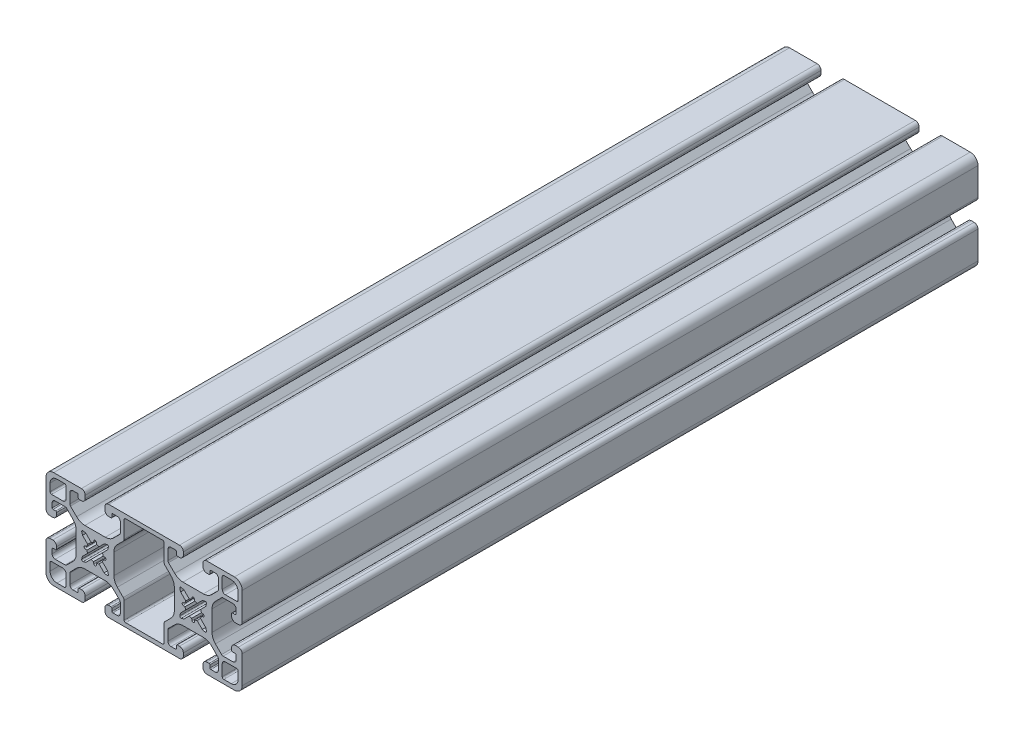
SolidWorks part; units mm, degrees
material "6105-T5 Aluminum"
ref_plane "Front Plane" through (0, 0, 0) normal (0, 0, 1) x (1, 0, 0)
ref_plane "Top Plane" through (0, 0, 0) normal (0, 1, 0) x (1, 0, 0)
ref_plane "Right Plane" through (0, 0, 0) normal (1, 0, 0) x (0, 0, -1)
sketch "Sketch1" plane through (0, 0, 0) normal (0, 0, 1) x (1, 0, 0)
  line L0 (-24, -18.4848) -> (-24, -17.255)
  line L1 (-26.474, -15.685) -> (-25.57, -15.685)
  line L2 (-36.83, -20) -> (-25.569, -20)
  line L3 (-26.855, -17.119) -> (-26.855, -16.066)
  line L4 (-40, -16.83) -> (-40, -5.57)
  line L5 (-29.015, -17.5) -> (-27.236, -17.5)
  line L6 (-38.43, -4) -> (-37.255, -4)
  line L7 (-30.285, -16.23) -> (-30.285, -12.2162)
  line L8 (-35.685, -5.57) -> (-35.685, -6.474)
  line L9 (-27.5137, -9.0762) -> (-30.0243, -11.5869)
  line L10 (-37.119, -6.855) -> (-36.066, -6.855)
  line L11 (-24.1549, -7.685) -> (-15.8451, -7.685)
  line L12 (-37.5, -9.015) -> (-37.5, -7.236)
  line L13 (-12.4863, -9.0762) -> (-9.9757, -11.5869)
  line L14 (-36.23, -10.285) -> (-32.2162, -10.285)
  line L15 (-9.715, -16.23) -> (-9.715, -12.2162)
  line L16 (-29.0762, -7.5137) -> (-31.5869, -10.0243)
  line L17 (-10.985, -17.5) -> (-12.764, -17.5)
  line L18 (-27.685, 4.1549) -> (-27.685, -4.1549)
  line L19 (-13.145, -17.119) -> (-13.145, -16.066)
  line L20 (-29.0762, 7.5137) -> (-31.5869, 10.0243)
  line L21 (-14.43, -15.685) -> (-13.526, -15.685)
  line L22 (-36.23, 10.285) -> (-32.2162, 10.285)
  line L23 (-16, -18.4848) -> (-16, -17.255)
  line L24 (-37.5, 9.015) -> (-37.5, 7.236)
  line L25 (14.43, -20) -> (-14.431, -20)
  line L26 (-37.119, 6.855) -> (-36.066, 6.855)
  line L27 (16, -17.255) -> (16, -18.43)
  line L28 (-35.685, 6.474) -> (-35.685, 5.57)
  line L29 (14.43, -15.685) -> (13.526, -15.685)
  line L30 (-38.43, 4) -> (-37.255, 4)
  line L31 (13.145, -17.119) -> (13.145, -16.066)
  line L32 (-40, 16.83) -> (-40, 5.57)
  line L33 (10.985, -17.5) -> (12.764, -17.5)
  line L34 (-36.83, 20) -> (-25.57, 20)
  line L35 (9.715, -16.23) -> (9.715, -12.2162)
  line L36 (-24, 18.43) -> (-24, 17.255)
  line L37 (12.4863, -9.0762) -> (9.9757, -11.5869)
  line L38 (-25.57, 15.685) -> (-26.474, 15.685)
  line L39 (24.1549, -7.685) -> (15.8451, -7.685)
  line L40 (-26.855, 17.119) -> (-26.855, 16.066)
  line L41 (27.5137, -9.0762) -> (30.0243, -11.5869)
  line L42 (-29.015, 17.5) -> (-27.236, 17.5)
  line L43 (30.285, -16.23) -> (30.285, -12.2162)
  line L44 (-30.285, 16.23) -> (-30.285, 12.2162)
  line L45 (29.015, -17.5) -> (27.236, -17.5)
  line L46 (-27.5137, 9.0762) -> (-30.0243, 11.5869)
  line L47 (26.855, -17.119) -> (26.855, -16.066)
  line L48 (-15.8451, 7.685) -> (-24.1549, 7.685)
  line L49 (26.474, -15.685) -> (25.57, -15.685)
  line L50 (-12.4863, 9.0762) -> (-9.9757, 11.5869)
  line L51 (24, -17.255) -> (24, -18.43)
  line L52 (-9.715, 16.23) -> (-9.715, 12.2162)
  line L53 (36.83, -20) -> (25.57, -20)
  line L54 (-10.985, 17.5) -> (-12.764, 17.5)
  line L55 (40, -16.83) -> (40, -5.57)
  line L56 (-13.145, 17.119) -> (-13.145, 16.066)
  line L57 (37.255, -4) -> (38.43, -4)
  line L58 (-13.526, 15.685) -> (-14.43, 15.685)
  line L59 (35.685, -5.57) -> (35.685, -6.474)
  line L60 (-16, 18.43) -> (-16, 17.255)
  line L61 (37.119, -6.855) -> (36.066, -6.855)
  line L62 (-14.43, 20) -> (14.43, 20)
  line L63 (37.5, -9.015) -> (37.5, -7.236)
  line L64 (16, 18.43) -> (16, 17.255)
  line L65 (36.23, -10.285) -> (32.2162, -10.285)
  line L66 (13.526, 15.685) -> (14.43, 15.685)
  line L67 (29.0762, -7.5137) -> (31.5869, -10.0243)
  line L68 (13.145, 17.119) -> (13.145, 16.066)
  line L69 (27.685, 4.1549) -> (27.685, -4.1549)
  line L70 (10.985, 17.5) -> (12.764, 17.5)
  line L71 (29.0762, 7.5137) -> (31.5869, 10.0243)
  line L72 (9.715, 16.23) -> (9.715, 12.2162)
  line L73 (36.23, 10.285) -> (32.2162, 10.285)
  line L74 (12.4863, 9.0762) -> (9.9757, 11.5869)
  line L75 (37.5, 9.015) -> (37.5, 7.236)
  line L76 (15.8451, 7.685) -> (24.1549, 7.685)
  line L77 (37.119, 6.855) -> (36.066, 6.855)
  line L78 (27.5137, 9.0762) -> (30.0243, 11.5869)
  line L79 (35.685, 6.474) -> (35.685, 5.57)
  line L80 (30.285, 16.23) -> (30.285, 12.2162)
  line L81 (37.255, 4) -> (38.43, 4)
  line L82 (29.015, 17.5) -> (27.236, 17.5)
  line L83 (40, 16.83) -> (40, 5.57)
  line L84 (26.855, 17.119) -> (26.855, 16.066)
  line L85 (36.83, 20) -> (25.57, 20)
  line L86 (25.57, 15.685) -> (26.474, 15.685)
  line L87 (24, 18.43) -> (24, 17.255)
  line L88 (35.545, -18.345) -> (32.4898, -18.345)
  line L89 (38.345, -12.4898) -> (38.345, -15.545)
  line L90 (31.8598, -17.715) -> (31.8598, -13.1298)
  line L91 (33.1298, -11.8598) -> (37.715, -11.8598)
  line L92 (8.1402, 17.715) -> (8.1402, 10.8233)
  line L93 (8.5122, 9.9253) -> (10.9238, 7.5137)
  line L94 (-7.5102, 18.345) -> (7.5102, 18.345)
  line L95 (12.315, 4.1549) -> (12.315, -4.1549)
  line L96 (-8.1402, 10.8233) -> (-8.1402, 17.715)
  line L97 (10.9238, -7.5137) -> (8.5122, -9.9253)
  line L98 (-10.9238, 7.5137) -> (-8.5122, 9.9253)
  line L99 (8.1402, -10.8233) -> (8.1402, -17.715)
  line L100 (-12.315, -4.1549) -> (-12.315, 4.1549)
  line L101 (7.5102, -18.345) -> (-7.5102, -18.345)
  line L102 (-8.5122, -9.9253) -> (-10.9238, -7.5137)
  line L103 (-8.1402, -17.715) -> (-8.1402, -10.8233)
  line L104 (-38.345, -15.545) -> (-38.345, -12.4898)
  line L105 (-32.4898, -18.345) -> (-35.545, -18.345)
  line L106 (-37.715, -11.8598) -> (-33.1298, -11.8598)
  line L107 (-31.8598, -13.1298) -> (-31.8598, -17.715)
  line L108 (-35.545, 18.345) -> (-32.4898, 18.345)
  line L109 (-38.345, 12.4898) -> (-38.345, 15.545)
  line L110 (-31.8598, 17.715) -> (-31.8598, 13.1298)
  line L111 (-33.1298, 11.8598) -> (-37.715, 11.8598)
  line L112 (38.345, 15.545) -> (38.345, 12.4898)
  line L113 (32.4898, 18.345) -> (35.545, 18.345)
  line L114 (37.715, 11.8598) -> (33.1298, 11.8598)
  line L115 (31.8598, 13.1298) -> (31.8598, 17.715)
  line L116 (-14.8737, -3.712) -> (-14.5607, -4.8481)
  line L117 (-16.9951, -1.5907) -> (-14.8737, -3.712)
  line L118 (-15.1519, -5.4393) -> (-16.288, -5.1263)
  line L119 (-16.288, -5.1263) -> (-18.4093, -3.0049)
  line L120 (-15.9124, -0.4923) -> (-16.6579, -0.625)
  line L121 (-19.375, -3.3421) -> (-19.5077, -4.0876)
  line L122 (-16.6579, 0.625) -> (-15.9124, 0.4923)
  line L123 (-20.4923, -4.0876) -> (-20.625, -3.3421)
  line L124 (-14.8737, 3.712) -> (-16.9951, 1.5907)
  line L125 (-14.5607, 4.8481) -> (-14.8737, 3.712)
  line L126 (-21.5907, -3.0049) -> (-23.712, -5.1263)
  line L127 (-23.712, -5.1263) -> (-24.8481, -5.4393)
  line L128 (-16.288, 5.1263) -> (-15.1519, 5.4393)
  line L129 (-18.4093, 3.0049) -> (-16.288, 5.1263)
  line L130 (-25.4393, -4.8481) -> (-25.1263, -3.712)
  line L131 (-25.1263, -3.712) -> (-23.0049, -1.5907)
  line L132 (-19.5077, 4.0876) -> (-19.375, 3.3421)
  line L133 (-23.3421, -0.625) -> (-24.0876, -0.4923)
  line L134 (-20.625, 3.3421) -> (-20.4923, 4.0876)
  line L135 (-24.0876, 0.4923) -> (-23.3421, 0.625)
  line L136 (-23.712, 5.1263) -> (-21.5907, 3.0049)
  line L137 (-24.8481, 5.4393) -> (-23.712, 5.1263)
  line L138 (-23.0049, 1.5907) -> (-25.1263, 3.712)
  line L139 (-25.1263, 3.712) -> (-25.4393, 4.8481)
  line L140 (25.1263, -3.712) -> (25.4393, -4.8481)
  line L141 (23.0049, -1.5907) -> (25.1263, -3.712)
  line L142 (24.8481, -5.4393) -> (23.712, -5.1263)
  line L143 (23.712, -5.1263) -> (21.5907, -3.0049)
  line L144 (24.0876, -0.4923) -> (23.3421, -0.625)
  line L145 (20.625, -3.3421) -> (20.4923, -4.0876)
  line L146 (23.3421, 0.625) -> (24.0876, 0.4923)
  line L147 (19.5077, -4.0876) -> (19.375, -3.3421)
  line L148 (25.1263, 3.712) -> (23.0049, 1.5907)
  line L149 (25.4393, 4.8481) -> (25.1263, 3.712)
  line L150 (18.4093, -3.0049) -> (16.288, -5.1263)
  line L151 (16.288, -5.1263) -> (15.1519, -5.4393)
  line L152 (23.712, 5.1263) -> (24.8481, 5.4393)
  line L153 (21.5907, 3.0049) -> (23.712, 5.1263)
  line L154 (14.5607, -4.8481) -> (14.8737, -3.712)
  line L155 (14.8737, -3.712) -> (16.9951, -1.5907)
  line L156 (20.4923, 4.0876) -> (20.625, 3.3421)
  line L157 (16.6579, -0.625) -> (15.9124, -0.4923)
  line L158 (19.375, 3.3421) -> (19.5077, 4.0876)
  line L159 (15.9124, 0.4923) -> (16.6579, 0.625)
  line L160 (16.288, 5.1263) -> (18.4093, 3.0049)
  line L161 (15.1519, 5.4393) -> (16.288, 5.1263)
  line L162 (16.9951, 1.5907) -> (14.8737, 3.712)
  line L163 (14.8737, 3.712) -> (14.5607, 4.8481)
  arc A0 (-24, -17.255) -> (-25.57, -15.685) centre (-25.57, -17.255) ccw
  arc A1 (-25.569, -20) -> (-24, -18.4848) centre (-25.569, -18.43) ccw
  arc A2 (-26.474, -15.685) -> (-26.855, -16.066) centre (-26.474, -16.066) ccw
  arc A3 (-40, -16.83) -> (-36.83, -20) centre (-36.83, -16.83) ccw
  arc A4 (-27.236, -17.5) -> (-26.855, -17.119) centre (-27.236, -17.119) ccw
  arc A5 (-38.43, -4) -> (-40, -5.57) centre (-38.43, -5.57) ccw
  arc A6 (-30.285, -16.23) -> (-29.015, -17.5) centre (-29.015, -16.23) ccw
  arc A7 (-35.685, -5.57) -> (-37.255, -4) centre (-37.255, -5.57) ccw
  arc A8 (-30.0243, -11.5869) -> (-30.285, -12.2162) centre (-29.395, -12.2162) ccw
  arc A9 (-36.066, -6.855) -> (-35.685, -6.474) centre (-36.066, -6.474) ccw
  arc A10 (-24.1549, -7.685) -> (-27.5137, -9.0762) centre (-24.1549, -12.435) ccw
  arc A11 (-37.119, -6.855) -> (-37.5, -7.236) centre (-37.119, -7.236) ccw
  arc A12 (-12.4863, -9.0762) -> (-15.8451, -7.685) centre (-15.8451, -12.435) ccw
  arc A13 (-37.5, -9.015) -> (-36.23, -10.285) centre (-36.23, -9.015) ccw
  arc A14 (-9.715, -12.2162) -> (-9.9757, -11.5869) centre (-10.605, -12.2162) ccw
  arc A15 (-32.2162, -10.285) -> (-31.5869, -10.0243) centre (-32.2162, -9.395) ccw
  arc A16 (-10.985, -17.5) -> (-9.715, -16.23) centre (-10.985, -16.23) ccw
  arc A17 (-29.0762, -7.5137) -> (-27.685, -4.1549) centre (-32.435, -4.1549) ccw
  arc A18 (-13.145, -17.119) -> (-12.764, -17.5) centre (-12.764, -17.119) ccw
  arc A19 (-27.685, 4.1549) -> (-29.0762, 7.5137) centre (-32.435, 4.1549) ccw
  arc A20 (-13.145, -16.066) -> (-13.526, -15.685) centre (-13.526, -16.066) ccw
  arc A21 (-31.5869, 10.0243) -> (-32.2162, 10.285) centre (-32.2162, 9.395) ccw
  arc A22 (-14.43, -15.685) -> (-16, -17.255) centre (-14.43, -17.255) ccw
  arc A23 (-36.23, 10.285) -> (-37.5, 9.015) centre (-36.23, 9.015) ccw
  arc A24 (-16, -18.4848) -> (-14.431, -20) centre (-14.431, -18.43) ccw
  arc A25 (-37.5, 7.236) -> (-37.119, 6.855) centre (-37.119, 7.236) ccw
  arc A26 (14.43, -20) -> (16, -18.43) centre (14.43, -18.43) ccw
  arc A27 (-35.685, 6.474) -> (-36.066, 6.855) centre (-36.066, 6.474) ccw
  arc A28 (16, -17.255) -> (14.43, -15.685) centre (14.43, -17.255) ccw
  arc A29 (-37.255, 4) -> (-35.685, 5.57) centre (-37.255, 5.57) ccw
  arc A30 (13.526, -15.685) -> (13.145, -16.066) centre (13.526, -16.066) ccw
  arc A31 (-40, 5.57) -> (-38.43, 4) centre (-38.43, 5.57) ccw
  arc A32 (12.764, -17.5) -> (13.145, -17.119) centre (12.764, -17.119) ccw
  arc A33 (-36.83, 20) -> (-40, 16.83) centre (-36.83, 16.83) ccw
  arc A34 (9.715, -16.23) -> (10.985, -17.5) centre (10.985, -16.23) ccw
  arc A35 (-24, 18.43) -> (-25.57, 20) centre (-25.57, 18.43) ccw
  arc A36 (9.9757, -11.5869) -> (9.715, -12.2162) centre (10.605, -12.2162) ccw
  arc A37 (-25.57, 15.685) -> (-24, 17.255) centre (-25.57, 17.255) ccw
  arc A38 (15.8451, -7.685) -> (12.4863, -9.0762) centre (15.8451, -12.435) ccw
  arc A39 (-26.855, 16.066) -> (-26.474, 15.685) centre (-26.474, 16.066) ccw
  arc A40 (27.5137, -9.0762) -> (24.1549, -7.685) centre (24.1549, -12.435) ccw
  arc A41 (-26.855, 17.119) -> (-27.236, 17.5) centre (-27.236, 17.119) ccw
  arc A42 (30.285, -12.2162) -> (30.0243, -11.5869) centre (29.395, -12.2162) ccw
  arc A43 (-29.015, 17.5) -> (-30.285, 16.23) centre (-29.015, 16.23) ccw
  arc A44 (29.015, -17.5) -> (30.285, -16.23) centre (29.015, -16.23) ccw
  arc A45 (-30.285, 12.2162) -> (-30.0243, 11.5869) centre (-29.395, 12.2162) ccw
  arc A46 (26.855, -17.119) -> (27.236, -17.5) centre (27.236, -17.119) ccw
  arc A47 (-27.5137, 9.0762) -> (-24.1549, 7.685) centre (-24.1549, 12.435) ccw
  arc A48 (26.855, -16.066) -> (26.474, -15.685) centre (26.474, -16.066) ccw
  arc A49 (-15.8451, 7.685) -> (-12.4863, 9.0762) centre (-15.8451, 12.435) ccw
  arc A50 (25.57, -15.685) -> (24, -17.255) centre (25.57, -17.255) ccw
  arc A51 (-9.9757, 11.5869) -> (-9.715, 12.2162) centre (-10.605, 12.2162) ccw
  arc A52 (24, -18.43) -> (25.57, -20) centre (25.57, -18.43) ccw
  arc A53 (-9.715, 16.23) -> (-10.985, 17.5) centre (-10.985, 16.23) ccw
  arc A54 (36.83, -20) -> (40, -16.83) centre (36.83, -16.83) ccw
  arc A55 (-12.764, 17.5) -> (-13.145, 17.119) centre (-12.764, 17.119) ccw
  arc A56 (40, -5.57) -> (38.43, -4) centre (38.43, -5.57) ccw
  arc A57 (-13.526, 15.685) -> (-13.145, 16.066) centre (-13.526, 16.066) ccw
  arc A58 (37.255, -4) -> (35.685, -5.57) centre (37.255, -5.57) ccw
  arc A59 (-16, 17.255) -> (-14.43, 15.685) centre (-14.43, 17.255) ccw
  arc A60 (35.685, -6.474) -> (36.066, -6.855) centre (36.066, -6.474) ccw
  arc A61 (-14.43, 20) -> (-16, 18.43) centre (-14.43, 18.43) ccw
  arc A62 (37.5, -7.236) -> (37.119, -6.855) centre (37.119, -7.236) ccw
  arc A63 (16, 18.43) -> (14.43, 20) centre (14.43, 18.43) ccw
  arc A64 (36.23, -10.285) -> (37.5, -9.015) centre (36.23, -9.015) ccw
  arc A65 (14.43, 15.685) -> (16, 17.255) centre (14.43, 17.255) ccw
  arc A66 (31.5869, -10.0243) -> (32.2162, -10.285) centre (32.2162, -9.395) ccw
  arc A67 (13.145, 16.066) -> (13.526, 15.685) centre (13.526, 16.066) ccw
  arc A68 (27.685, -4.1549) -> (29.0762, -7.5137) centre (32.435, -4.1549) ccw
  arc A69 (13.145, 17.119) -> (12.764, 17.5) centre (12.764, 17.119) ccw
  arc A70 (29.0762, 7.5137) -> (27.685, 4.1549) centre (32.435, 4.1549) ccw
  arc A71 (10.985, 17.5) -> (9.715, 16.23) centre (10.985, 16.23) ccw
  arc A72 (32.2162, 10.285) -> (31.5869, 10.0243) centre (32.2162, 9.395) ccw
  arc A73 (9.715, 12.2162) -> (9.9757, 11.5869) centre (10.605, 12.2162) ccw
  arc A74 (37.5, 9.015) -> (36.23, 10.285) centre (36.23, 9.015) ccw
  arc A75 (12.4863, 9.0762) -> (15.8451, 7.685) centre (15.8451, 12.435) ccw
  arc A76 (37.119, 6.855) -> (37.5, 7.236) centre (37.119, 7.236) ccw
  arc A77 (24.1549, 7.685) -> (27.5137, 9.0762) centre (24.1549, 12.435) ccw
  arc A78 (36.066, 6.855) -> (35.685, 6.474) centre (36.066, 6.474) ccw
  arc A79 (30.0243, 11.5869) -> (30.285, 12.2162) centre (29.395, 12.2162) ccw
  arc A80 (35.685, 5.57) -> (37.255, 4) centre (37.255, 5.57) ccw
  arc A81 (30.285, 16.23) -> (29.015, 17.5) centre (29.015, 16.23) ccw
  arc A82 (38.43, 4) -> (40, 5.57) centre (38.43, 5.57) ccw
  arc A83 (27.236, 17.5) -> (26.855, 17.119) centre (27.236, 17.119) ccw
  arc A84 (40, 16.83) -> (36.83, 20) centre (36.83, 16.83) ccw
  arc A85 (26.474, 15.685) -> (26.855, 16.066) centre (26.474, 16.066) ccw
  arc A86 (25.57, 20) -> (24, 18.43) centre (25.57, 18.43) ccw
  arc A87 (24, 17.255) -> (25.57, 15.685) centre (25.57, 17.255) ccw
  arc A88 (35.545, -18.345) -> (38.345, -15.545) centre (35.545, -15.545) ccw
  arc A89 (31.8598, -17.715) -> (32.4898, -18.345) centre (32.4898, -17.715) ccw
  arc A90 (38.345, -12.4898) -> (37.715, -11.8598) centre (37.715, -12.4898) ccw
  arc A91 (33.1298, -11.8598) -> (31.8598, -13.1298) centre (33.1298, -13.1298) ccw
  arc A92 (8.1402, 10.8233) -> (8.5122, 9.9253) centre (9.4102, 10.8233) ccw
  arc A93 (8.1402, 17.715) -> (7.5102, 18.345) centre (7.5102, 17.715) ccw
  arc A94 (12.315, 4.1549) -> (10.9238, 7.5137) centre (7.565, 4.1549) ccw
  arc A95 (-7.5102, 18.345) -> (-8.1402, 17.715) centre (-7.5102, 17.715) ccw
  arc A96 (10.9238, -7.5137) -> (12.315, -4.1549) centre (7.565, -4.1549) ccw
  arc A97 (-8.5122, 9.9253) -> (-8.1402, 10.8233) centre (-9.4102, 10.8233) ccw
  arc A98 (8.5122, -9.9253) -> (8.1402, -10.8233) centre (9.4102, -10.8233) ccw
  arc A99 (-10.9238, 7.5137) -> (-12.315, 4.1549) centre (-7.565, 4.1549) ccw
  arc A100 (7.5102, -18.345) -> (8.1402, -17.715) centre (7.5102, -17.715) ccw
  arc A101 (-12.315, -4.1549) -> (-10.9238, -7.5137) centre (-7.565, -4.1549) ccw
  arc A102 (-8.1402, -17.715) -> (-7.5102, -18.345) centre (-7.5102, -17.715) ccw
  arc A103 (-8.1402, -10.8233) -> (-8.5122, -9.9253) centre (-9.4102, -10.8233) ccw
  arc A104 (-38.345, -15.545) -> (-35.545, -18.345) centre (-35.545, -15.545) ccw
  arc A105 (-37.715, -11.8598) -> (-38.345, -12.4898) centre (-37.715, -12.4898) ccw
  arc A106 (-32.4898, -18.345) -> (-31.8598, -17.715) centre (-32.4898, -17.715) ccw
  arc A107 (-31.8598, -13.1298) -> (-33.1298, -11.8598) centre (-33.1298, -13.1298) ccw
  arc A108 (-35.545, 18.345) -> (-38.345, 15.545) centre (-35.545, 15.545) ccw
  arc A109 (-31.8598, 17.715) -> (-32.4898, 18.345) centre (-32.4898, 17.715) ccw
  arc A110 (-38.345, 12.4898) -> (-37.715, 11.8598) centre (-37.715, 12.4898) ccw
  arc A111 (-33.1298, 11.8598) -> (-31.8598, 13.1298) centre (-33.1298, 13.1298) ccw
  arc A112 (38.345, 15.545) -> (35.545, 18.345) centre (35.545, 15.545) ccw
  arc A113 (37.715, 11.8598) -> (38.345, 12.4898) centre (37.715, 12.4898) ccw
  arc A114 (32.4898, 18.345) -> (31.8598, 17.715) centre (32.4898, 17.715) ccw
  arc A115 (31.8598, 13.1298) -> (33.1298, 11.8598) centre (33.1298, 13.1298) ccw
  arc A116 (-15.1519, -5.4393) -> (-14.5607, -4.8481) centre (-15.0503, -4.9497) ccw
  arc A117 (-16.9951, -1.5907) -> (-16.6579, -0.625) centre (-20, 0) ccw
  arc A118 (-19.375, -3.3421) -> (-18.4093, -3.0049) centre (-20, 0) ccw
  arc A119 (-15.9124, -0.4923) -> (-15.9124, 0.4923) centre (-16, 0) ccw
  arc A120 (-20.4923, -4.0876) -> (-19.5077, -4.0876) centre (-20, -4) ccw
  arc A121 (-16.6579, 0.625) -> (-16.9951, 1.5907) centre (-20, 0) ccw
  arc A122 (-21.5907, -3.0049) -> (-20.625, -3.3421) centre (-20, 0) ccw
  arc A123 (-14.5607, 4.8481) -> (-15.1519, 5.4393) centre (-15.0503, 4.9497) ccw
  arc A124 (-25.4393, -4.8481) -> (-24.8481, -5.4393) centre (-24.9497, -4.9497) ccw
  arc A125 (-18.4093, 3.0049) -> (-19.375, 3.3421) centre (-20, 0) ccw
  arc A126 (-23.3421, -0.625) -> (-23.0049, -1.5907) centre (-20, 0) ccw
  arc A127 (-19.5077, 4.0876) -> (-20.4923, 4.0876) centre (-20, 4) ccw
  arc A128 (-24.0876, 0.4923) -> (-24.0876, -0.4923) centre (-24, 0) ccw
  arc A129 (-20.625, 3.3421) -> (-21.5907, 3.0049) centre (-20, 0) ccw
  arc A130 (-23.0049, 1.5907) -> (-23.3421, 0.625) centre (-20, 0) ccw
  arc A131 (-24.8481, 5.4393) -> (-25.4393, 4.8481) centre (-24.9497, 4.9497) ccw
  arc A132 (24.8481, -5.4393) -> (25.4393, -4.8481) centre (24.9497, -4.9497) ccw
  arc A133 (23.0049, -1.5907) -> (23.3421, -0.625) centre (20, 0) ccw
  arc A134 (20.625, -3.3421) -> (21.5907, -3.0049) centre (20, 0) ccw
  arc A135 (24.0876, -0.4923) -> (24.0876, 0.4923) centre (24, 0) ccw
  arc A136 (19.5077, -4.0876) -> (20.4923, -4.0876) centre (20, -4) ccw
  arc A137 (23.3421, 0.625) -> (23.0049, 1.5907) centre (20, 0) ccw
  arc A138 (18.4093, -3.0049) -> (19.375, -3.3421) centre (20, 0) ccw
  arc A139 (25.4393, 4.8481) -> (24.8481, 5.4393) centre (24.9497, 4.9497) ccw
  arc A140 (14.5607, -4.8481) -> (15.1519, -5.4393) centre (15.0503, -4.9497) ccw
  arc A141 (21.5907, 3.0049) -> (20.625, 3.3421) centre (20, 0) ccw
  arc A142 (16.6579, -0.625) -> (16.9951, -1.5907) centre (20, 0) ccw
  arc A143 (20.4923, 4.0876) -> (19.5077, 4.0876) centre (20, 4) ccw
  arc A144 (15.9124, 0.4923) -> (15.9124, -0.4923) centre (16, 0) ccw
  arc A145 (19.375, 3.3421) -> (18.4093, 3.0049) centre (20, 0) ccw
  arc A146 (16.9951, 1.5907) -> (16.6579, 0.625) centre (20, 0) ccw
  arc A147 (15.1519, 5.4393) -> (14.5607, 4.8481) centre (15.0503, 4.9497) ccw
extrude "Extrude1" add sketch "Sketch1" against normal blind 300
